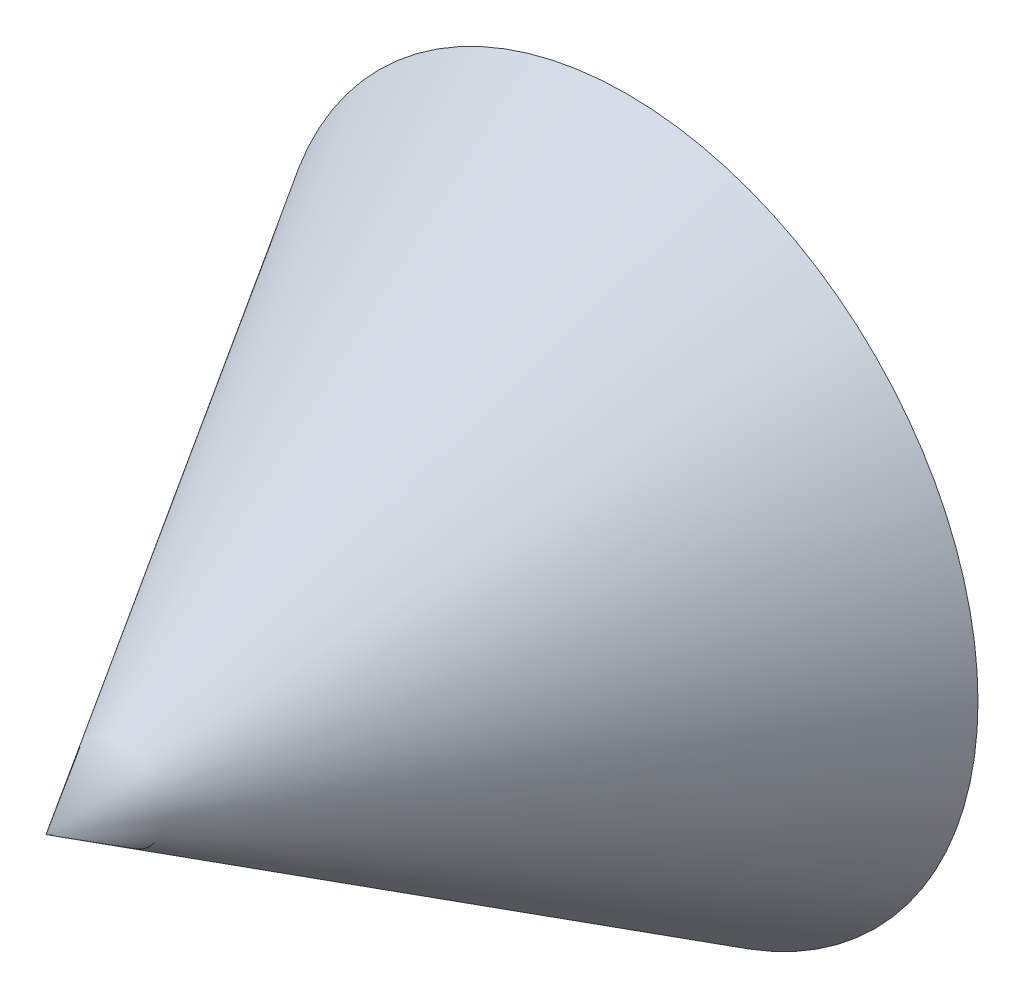
SolidWorks part; units mm, degrees
ref_plane "Front Plane" through (0, 0, 0) normal (0, 0, 1) x (1, 0, 0)
ref_plane "Top Plane" through (0, 0, 0) normal (0, 1, 0) x (1, 0, 0)
ref_plane "Right Plane" through (0, 0, 0) normal (1, 0, 0) x (0, 0, -1)
sketch "Sketch1" plane through (0, 0, 0) normal (0, 1, 0) x (1, 0, 0)
  line L0 (0, 0) -> (0, 200)
  line L1 (0, 200) -> (120.6477, 200)
  line L2 (120.6477, 200) -> (0, 0)
  dimension "D1" = 31.1
  dimension "D2" = 200
revolve "Revolve2" add sketch "Sketch1" angle 360 about L0
sketch "Sketch2" plane through (0, 0, 0) normal (0, 0, 1) x (1, 0, 0)
  circle A0 centre (0, 0) radius 17.5
  dimension "D1" = 35
